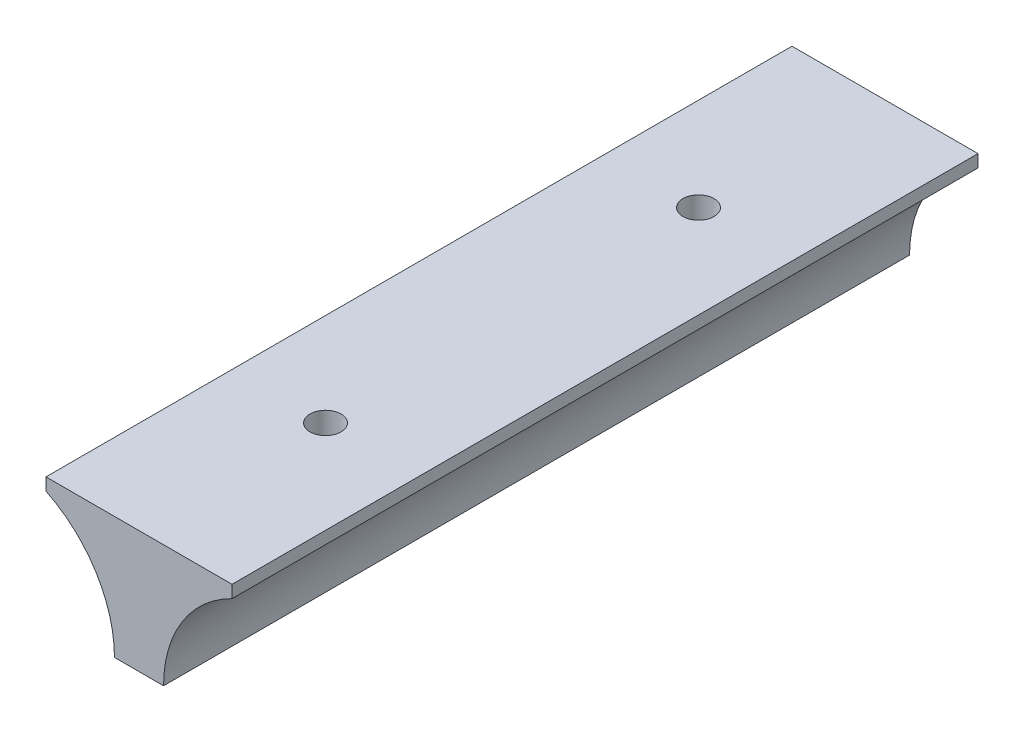
SolidWorks part; units mm, degrees
ref_plane "Front" through (0, 0, 0) normal (0, 0, 1) x (1, 0, 0)
ref_plane "Top" through (0, 0, 0) normal (0, 1, 0) x (1, 0, 0)
ref_plane "Right" through (0, 0, 0) normal (1, 0, 0) x (0, 0, -1)
sketch "Sketch1" plane through (0, 0, 0) normal (0, 0, 1) x (1, 0, 0)
  line L0 (-1.975, 0) -> (1.975, 0)
  line L1 (7.4814, 8.825) -> (7.4814, 9.825)
  line L2 (7.4814, 9.825) -> (-7.4814, 9.825)
  line L3 (-7.4814, 9.825) -> (-7.4814, 8.825)
  arc A0 (1.975, 0) -> (7.4814, 8.825) centre (11.8, 0) cw
  arc A1 (-1.975, 0) -> (-7.4814, 8.825) centre (-11.8, 0) ccw
  point P9 (0, 0)
  point P10 (0, 9.825)
  dimension "D1" = 9.825
  dimension "D2" = 9.825
  dimension "D3" = 3.95
  dimension "D4" = 1
extrude "Boss-Extrude1" add sketch "Sketch1" along normal blind 60
sketch "Sketch2" plane through (0, 9.825, 0) normal (0, 1, 0) x (1, 0, 0)
  line L0 (0, -60) -> (0, 0) construction
  line L1 (7.4814, -60) -> (-7.4814, -60) construction
  line L2 (7.4814, 0) -> (-7.4814, 0) construction
  point P6 (0, -45)
  point P7 (0, -15)
  dimension "D1" = 15
  dimension "D2" = 15
hole_wizard "Ø2.5mm Dowel Hole1" positions "3DSketch1" profile "Sketch3" hole size "Ø2.5" standard "ANSI Metric" end condition up to next
sketch3d "3DSketch1"
  point P0 (0, 9.825, 45)
  point P3 (0, 9.825, 15)
sketch "Sketch3" plane through (0, 9.825, 45) normal (1, 0, 0) x (0, 0, 1)
  line L0 (0, 0) -> (0, 9.825)
  line L1 (0, 9.825) -> (1.25, 9.825)
  line L2 (1.25, 9.825) -> (1.25, 0)
  line L5 (1.25, 0) -> (0, 0)
  line L11 (0, -6.35) -> (0, 107.95) construction
  dimension "Thru Hole Dia." = 2.5
  dimension "Thru Hole Depth" = 9.825
